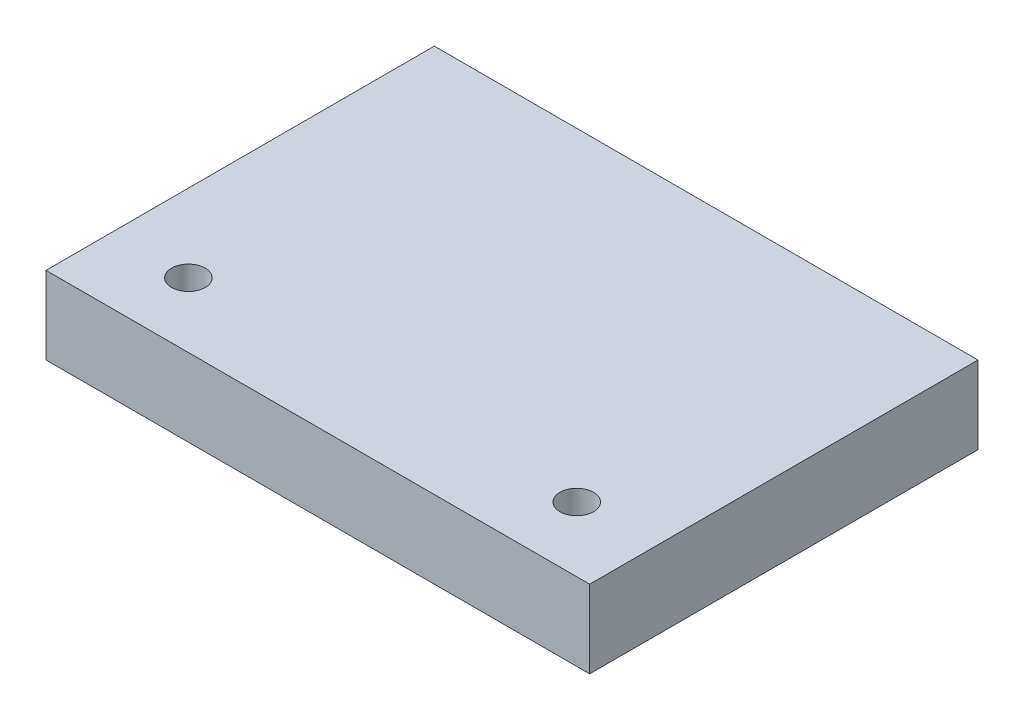
SolidWorks part; units mm, degrees
ref_plane "前视基准面" through (0, 0, 0) normal (0, 0, 1) x (1, 0, 0)
ref_plane "上视基准面" through (0, 0, 0) normal (0, 1, 0) x (1, 0, 0)
ref_plane "右视基准面" through (0, 0, 0) normal (1, 0, 0) x (0, 0, -1)
other "Configuration Table"
sketch "草图1" plane through (0, 0, 0) normal (0, 1, 0) x (1, 0, 0)
  line L5 (-10.5, 7.5) -> (10.5, 7.5)
  line L6 (-10.5, 7.5) -> (-10.5, -7.5)
  line L7 (-10.5, -7.5) -> (10.5, -7.5)
  line L8 (10.5, 7.5) -> (10.5, -7.5)
  line L9 (-10.5, 7.5) -> (10.5, -7.5) construction
  line L10 (-10.5, -7.5) -> (10.5, 7.5) construction
  point P0 (0, 0)
  dimension "D1" = 21
  dimension "D2" = 15
extrude "凸台-拉伸1" add sketch "草图1" along normal blind 3
sketch "草图2" plane through (0, 3, 0) normal (0, 1, 0) x (1, 0, 0)
  line L0 (-7.5, -5) -> (7.5, -5)
  line L1 (10.5, -7.5) -> (10.5, 7.5) construction
  line L2 (-10.5, 7.5) -> (-10.5, -7.5) construction
  line L3 (-10.5, -7.5) -> (10.5, -7.5) construction
  line L4 (8.7413, -7.15) -> (9.9826, -5)
  line L5 (-6.2587, -7.15) -> (-5.0174, -5)
  line L6 (-5.0174, -5) -> (-6.2587, -2.85)
  line L7 (-6.2587, -2.85) -> (-8.7413, -2.85)
  line L8 (-8.7413, -2.85) -> (-9.9826, -5)
  line L9 (-9.9826, -5) -> (-8.7413, -7.15)
  line L10 (-8.7413, -7.15) -> (-6.2587, -7.15)
  line L17 (9.9826, -5) -> (8.7413, -2.85)
  line L18 (8.7413, -2.85) -> (6.2587, -2.85)
  line L19 (6.2587, -2.85) -> (5.0174, -5)
  line L20 (5.0174, -5) -> (6.2587, -7.15)
  line L21 (6.2587, -7.15) -> (8.7413, -7.15)
  circle A0 centre (-7.5, -5) radius 2.15 construction
  circle A1 centre (7.5, -5) radius 2.15 construction
  dimension "D1" = 3
  dimension "D2" = 3
  dimension "D3" = 2.5
  dimension "D4" = 4.3
  dimension "D5" = 2
hole_wizard "孔1" positions "草图3" profile "草图4" legacy end condition up to next
sketch "草图3" plane through (0, 3, 0) normal (0, 1, 0) x (1, 0, 0)
  point P0 (-7.5, -5)
  point P3 (7.5, -5)
sketch "草图4" plane through (-7.5, 3, 5) normal (1, 0, 0) x (0, 0, 1)
  line L0 (0, 0) -> (0, 3)
  line L1 (0, 3) -> (0.65, 3)
  line L2 (0.65, 3) -> (0.65, 0)
  line L3 (0.65, 0) -> (0, 0)
  line L4 (0, 110) -> (0, -10) construction
  dimension "直径" = 1.3
  dimension "深度" = 3
